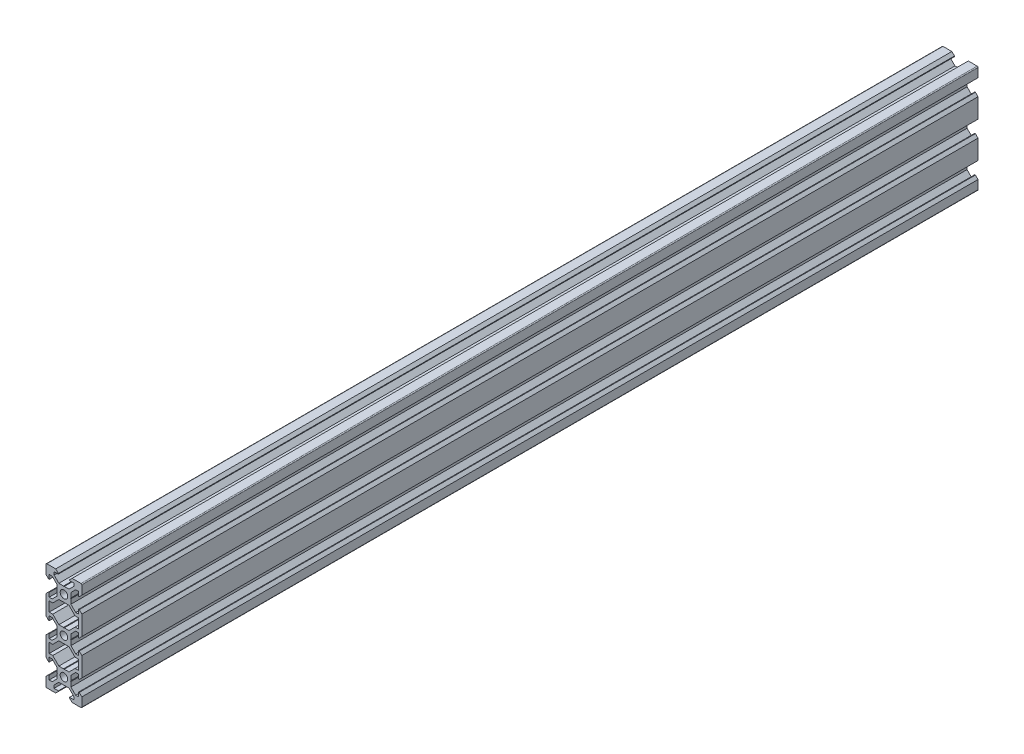
SolidWorks part; units mm, degrees
material "6063-T5"
ref_plane "Front Plane" through (0, 0, 0) normal (0, 0, 1) x (1, 0, 0)
ref_plane "Top Plane" through (0, 0, 0) normal (0, 1, 0) x (1, 0, 0)
ref_plane "Right Plane" through (0, 0, 0) normal (1, 0, 0) x (0, 0, -1)
sketch "Sketch2" plane through (0, 0, 0) normal (0, 0, 1) x (1, 0, 0)
  line L0 (-9.5, 10) -> (-4.58, 10)
  line L1 (-10, 10) -> (10, 10) construction
  line L2 (-10, 10) -> (-10, -10) construction
  line L3 (-10, -10) -> (10, -10) construction
  line L4 (10, 10) -> (10, -10) construction
  line L5 (-10, 10) -> (10, -10) construction
  line L6 (-10, -10) -> (10, 10) construction
  line L7 (-2.84, 3.9) -> (-0.21, 3.9)
  line L8 (-3.9, 2.84) -> (-3.9, 0.21)
  line L11 (-3.9, 3.9) -> (3.9, -3.9) construction
  line L12 (-3.9, -3.9) -> (3.9, 3.9) construction
  line L15 (-3.13, 8.2) -> (-5.5, 8.2)
  line L16 (-5.5, 8.2) -> (-5.5, 6.56)
  line L17 (0, 10) -> (0, -10) construction
  line L18 (-10, 0) -> (10, 0) construction
  line L20 (-10, 9.5) -> (-10, 4.58)
  line L21 (-10, 4.58) -> (-8.55, 3.13)
  line L22 (-8.55, 3.13) -> (-8.2, 3.13)
  line L27 (6.56, 5.5) -> (3.9, 2.84)
  line L30 (4.58, 10) -> (3.13, 8.55)
  line L35 (10, 4.58) -> (8.55, 3.13)
  line L36 (10, 9.5) -> (10, 4.58)
  line L37 (8.55, 3.13) -> (8.2, 3.13)
  line L40 (8.2, -5.5) -> (6.56, -5.5)
  line L41 (8.2, -3.13) -> (8.2, -5.5)
  line L42 (10, -4.58) -> (8.55, -3.13)
  line L43 (8.55, -3.13) -> (8.2, -3.13)
  line L44 (10, -10) -> (10, -4.58)
  line L57 (-8.2, -5.5) -> (-6.56, -5.5)
  line L58 (-8.2, -3.13) -> (-8.2, -5.5)
  line L59 (-10, -4.58) -> (-8.55, -3.13)
  line L60 (-10, -10) -> (-10, -4.58)
  line L61 (-8.55, -3.13) -> (-8.2, -3.13)
  line L62 (-0.21, 3.9) -> (0, 3.69)
  line L63 (0, 3.69) -> (0.21, 3.9)
  line L64 (0.21, 3.9) -> (2.84, 3.9)
  line L65 (3.69, 0) -> (3.9, -0.21)
  line L66 (3.9, 0.21) -> (3.69, 0)
  line L68 (0.21, -3.9) -> (0, -3.69)
  line L71 (3.9, -0.21) -> (3.9, -2.84)
  line L72 (-3.9, -0.21) -> (-3.9, -2.84)
  line L74 (-8.2, -7.3) -> (-8.2, -12.7)
  line L75 (-3.9, -39.79) -> (-3.69, -40)
  line L76 (-3.69, -40) -> (-3.9, -40.21)
  line L77 (-4.58, -10) -> (-3.13, -8.55) [skipped]
  line L78 (-0.21, -36.1) -> (0, -36.31)
  line L79 (-10, -10) -> (-4.58, -10) [skipped]
  line L80 (-2.84, -3.9) -> (-6.24, -7.3)
  line L82 (-8.2, -7.3) -> (-6.24, -7.3)
  line L84 (0, -36.31) -> (0.21, -36.1)
  line L85 (3.9, -39.79) -> (3.69, -40)
  line L86 (3.69, -40) -> (3.9, -40.21)
  line L87 (-0.21, -43.9) -> (0, -43.69)
  line L88 (0, -43.69) -> (0.21, -43.9)
  line L89 (-3.9, -39.79) -> (-3.9, -37.16)
  line L90 (2.84, -3.9) -> (6.24, -7.3)
  line L91 (8.2, -7.3) -> (8.2, -10)
  line L92 (6.24, -7.3) -> (8.2, -7.3)
  line L94 (-2.84, -16.1) -> (-0.21, -16.1)
  line L95 (-3.9, -17.16) -> (-3.9, -19.79)
  line L96 (-2.84, -23.9) -> (-0.21, -23.9)
  line L97 (3.9, -17.16) -> (3.9, -19.79)
  line L98 (2.84, -16.1) -> (6.24, -12.7)
  line L99 (-2.84, -16.1) -> (-6.24, -12.7)
  line L100 (0.21, -36.1) -> (2.84, -36.1)
  line L101 (8.2, -10) -> (8.2, -12.7)
  line L102 (6.24, -12.7) -> (8.2, -12.7)
  line L103 (-10, -10) -> (-10, -15.42)
  line L104 (-10, -15.42) -> (-8.55, -16.87)
  line L105 (-8.55, -16.87) -> (-8.2, -16.87)
  line L106 (-8.2, -16.87) -> (-8.2, -14.5)
  line L107 (-8.2, -14.5) -> (-6.56, -14.5)
  line L108 (-6.56, -14.5) -> (-3.9, -17.16)
  line L109 (-8.2, -12.7) -> (-6.24, -12.7)
  line L110 (6.56, -14.5) -> (3.9, -17.16)
  line L111 (4.58, -50) -> (3.13, -48.55)
  line L113 (-10, -30) -> (-10, -50) construction
  line L114 (-10, -50) -> (10, -50) construction
  line L115 (10, -30) -> (10, -50) construction
  line L116 (8.2, -14.5) -> (6.56, -14.5)
  line L117 (8.2, -16.87) -> (8.2, -14.5)
  line L118 (10, -15.42) -> (8.55, -16.87)
  line L119 (10, -10) -> (10, -15.42)
  line L120 (8.55, -16.87) -> (8.2, -16.87)
  line L121 (6.56, -25.5) -> (3.9, -22.84)
  line L122 (8.2, -25.5) -> (6.56, -25.5)
  line L123 (8.2, -23.13) -> (8.2, -25.5)
  line L124 (10, -24.58) -> (8.55, -23.13)
  line L125 (8.55, -23.13) -> (8.2, -23.13)
  line L126 (10, -30) -> (10, -24.58)
  line L127 (-6.56, -25.5) -> (-3.9, -22.84)
  line L128 (-8.2, -25.5) -> (-6.56, -25.5)
  line L129 (-8.2, -23.13) -> (-8.2, -25.5)
  line L130 (-10, -24.58) -> (-8.55, -23.13)
  line L131 (-10, -30) -> (-10, -24.58)
  line L132 (-8.55, -23.13) -> (-8.2, -23.13)
  line L133 (-0.21, -16.1) -> (0, -16.31)
  line L134 (0, -16.31) -> (0.21, -16.1)
  line L135 (0.21, -16.1) -> (2.84, -16.1)
  line L136 (3.69, -20) -> (3.9, -20.21)
  line L137 (3.9, -19.79) -> (3.69, -20)
  line L138 (0, -23.69) -> (-0.21, -23.9)
  line L139 (0.21, -23.9) -> (0, -23.69)
  line L140 (-3.69, -20) -> (-3.9, -19.79)
  line L141 (-3.9, -20.21) -> (-3.69, -20)
  line L142 (3.9, -20.21) -> (3.9, -22.84)
  line L143 (-3.9, -20.21) -> (-3.9, -22.84)
  line L144 (0.21, -23.9) -> (2.84, -23.9)
  line L145 (-2.84, -23.9) -> (-6.24, -27.3)
  line L146 (-8.2, -27.3) -> (-8.2, -32.7)
  line L147 (-8.2, -27.3) -> (-6.24, -27.3)
  line L148 (2.84, -23.9) -> (6.24, -27.3)
  line L149 (8.2, -27.3) -> (8.2, -30)
  line L150 (6.24, -27.3) -> (8.2, -27.3)
  line L151 (-10, -10) -> (10, -10) construction
  line L152 (-10, -10) -> (-10, -30) construction
  line L153 (-10, -30) -> (10, -30) construction
  line L154 (10, -10) -> (10, -30) construction
  line L155 (-10, -10) -> (10, -30) construction
  line L156 (-10, -30) -> (10, -10) construction
  line L157 (-3.9, -16.1) -> (3.9, -23.9) construction
  line L158 (-3.9, -23.9) -> (3.9, -16.1) construction
  line L159 (0, -10) -> (0, -30) construction
  line L160 (-10, -20) -> (10, -20) construction
  line L161 (3.9, -39.79) -> (3.9, -37.16)
  line L162 (0.21, -43.9) -> (2.84, -43.9)
  line L163 (-2.84, -3.9) -> (-0.21, -3.9)
  line L164 (3.9, 2.84) -> (3.9, 0.21)
  line L165 (-4.58, 10) -> (-3.13, 8.55)
  line L166 (-3.13, 8.55) -> (-3.13, 8.2)
  line L169 (-5.5, 6.56) -> (-2.84, 3.9)
  line L173 (-8.2, 3.13) -> (-8.2, 5.5)
  line L174 (-8.2, 5.5) -> (-6.56, 5.5)
  line L175 (-6.56, 5.5) -> (-3.9, 2.84)
  line L176 (5.5, 6.56) -> (2.84, 3.9)
  line L178 (5.5, 8.2) -> (5.5, 6.56)
  line L179 (3.13, 8.2) -> (5.5, 8.2)
  line L181 (3.13, 8.55) -> (3.13, 8.2)
  line L182 (8.2, 5.5) -> (6.56, 5.5)
  line L183 (8.2, 3.13) -> (8.2, 5.5)
  line L187 (6.56, -5.5) -> (3.9, -2.84)
  line L193 (-6.56, -5.5) -> (-3.9, -2.84)
  line L204 (0, -3.69) -> (-0.21, -3.9)
  line L206 (-3.69, 0) -> (-3.9, 0.21)
  line L207 (-3.9, -0.21) -> (-3.69, 0)
  line L210 (0.21, -3.9) -> (2.84, -3.9)
  line L213 (-10, 10) -> (-10, -10) construction
  line L214 (10, 10) -> (10, -10) construction
  line L215 (-10, 10) -> (10, -10) construction
  line L216 (-10, -10) -> (10, 10) construction
  line L217 (-3.9, 3.9) -> (3.9, -3.9) construction
  line L218 (-3.9, -3.9) -> (3.9, 3.9) construction
  line L219 (0, 10) -> (0, -10) construction
  line L220 (-10, 0) -> (10, 0) construction
  line L222 (9.5, 10) -> (4.58, 10)
  line L227 (3.13, -48.55) -> (3.13, -48.2)
  line L228 (3.13, -48.2) -> (5.5, -48.2)
  line L229 (5.5, -48.2) -> (5.5, -46.56)
  line L230 (-10, -50) -> (10, -30) construction
  line L231 (-10, -30) -> (10, -50) construction
  line L232 (0, -30) -> (0, -50) construction
  line L233 (-10, -40) -> (10, -40) construction
  line L234 (5.5, -46.56) -> (2.84, -43.9)
  line L235 (-2.84, -43.9) -> (-0.21, -43.9)
  line L236 (-3.9, -42.84) -> (-3.9, -40.21)
  line L237 (-2.84, -36.1) -> (-0.21, -36.1)
  line L238 (3.9, -42.84) -> (3.9, -40.21)
  line L239 (-3.9, -43.9) -> (3.9, -36.1) construction
  line L240 (-3.9, -36.1) -> (3.9, -43.9) construction
  line L241 (4.58, -50) -> (9.5, -50)
  line L242 (6.56, -45.5) -> (3.9, -42.84)
  line L243 (8.2, -45.5) -> (6.56, -45.5)
  line L244 (8.2, -43.13) -> (8.2, -45.5)
  line L245 (8.55, -43.13) -> (8.2, -43.13)
  line L246 (10, -44.58) -> (8.55, -43.13)
  line L247 (10, -44.58) -> (10, -49.5)
  line L248 (-4.58, -50) -> (-3.13, -48.55)
  line L249 (-3.13, -48.55) -> (-3.13, -48.2)
  line L250 (-3.13, -48.2) -> (-5.5, -48.2)
  line L251 (-5.5, -48.2) -> (-5.5, -46.56)
  line L252 (-5.5, -46.56) -> (-2.84, -43.9)
  line L253 (-4.58, -50) -> (-9.5, -50)
  line L254 (-8.55, -43.13) -> (-8.2, -43.13)
  line L255 (-6.56, -45.5) -> (-3.9, -42.84)
  line L256 (-8.2, -45.5) -> (-6.56, -45.5)
  line L257 (-8.2, -43.13) -> (-8.2, -45.5)
  line L258 (-10, -44.58) -> (-10, -49.5)
  line L259 (-10, -44.58) -> (-8.55, -43.13)
  line L260 (-8.2, -32.7) -> (-6.24, -32.7)
  line L261 (-2.84, -36.1) -> (-6.24, -32.7)
  line L262 (2.84, -36.1) -> (6.24, -32.7)
  line L263 (6.24, -32.7) -> (8.2, -32.7)
  line L264 (8.2, -32.7) -> (8.2, -30)
  line L265 (8.55, -36.87) -> (8.2, -36.87)
  line L266 (-8.55, -36.87) -> (-8.2, -36.87)
  line L267 (8.2, -36.87) -> (8.2, -34.5)
  line L268 (-8.2, -36.87) -> (-8.2, -34.5)
  line L269 (-8.2, -34.5) -> (-6.56, -34.5)
  line L270 (8.2, -34.5) -> (6.56, -34.5)
  line L271 (-6.56, -34.5) -> (-3.9, -37.16)
  line L272 (6.56, -34.5) -> (3.9, -37.16)
  line L273 (10, -35.42) -> (8.55, -36.87)
  line L274 (-10, -35.42) -> (-8.55, -36.87)
  line L275 (-10, -30) -> (-10, -35.42)
  line L276 (10, -30) -> (10, -35.42)
  line L307 (10, 10) -> (4.58, 10) [skipped]
  line L308 (-2.84, 3.9) -> (-0.21, 3.9) [skipped]
  line L309 (0.21, 3.9) -> (2.84, 3.9) [skipped]
  line L310 (-3.9, 2.84) -> (-3.9, 0.21) [skipped]
  line L311 (-3.9, -0.21) -> (-3.9, -2.84) [skipped]
  line L312 (3.9, -0.21) -> (3.9, -2.84) [skipped]
  line L313 (10, -4.58) -> (8.55, -3.13) [skipped]
  line L316 (-10, 10) -> (-10, 4.58) [skipped]
  line L317 (-10, -10) -> (-10, -4.58) [skipped]
  line L318 (-10, 4.58) -> (-8.55, 3.13) [skipped]
  line L319 (-8.55, 3.13) -> (-8.2, 3.13) [skipped]
  line L320 (8.55, 3.13) -> (8.2, 3.13) [skipped]
  line L321 (-8.2, -3.13) -> (-8.2, -5.5) [skipped]
  line L323 (2.84, -3.9) -> (6.24, -7.3) [skipped]
  line L324 (6.56, 5.5) -> (3.9, 2.84) [skipped]
  line L325 (-2.84, -3.9) -> (-6.24, -7.3) [skipped]
  line L326 (-10, -4.58) -> (-8.55, -3.13) [skipped]
  line L328 (8.2, -7.3) -> (8.2, -10) [skipped]
  line L329 (8.2, -3.13) -> (8.2, -5.5) [skipped]
  line L331 (10, 4.58) -> (8.55, 3.13) [skipped]
  line L332 (10, 10) -> (10, 4.58) [skipped]
  line L333 (10, -10) -> (10, -4.58) [skipped]
  line L334 (8.2, -5.5) -> (6.56, -5.5) [skipped]
  line L335 (-8.2, -5.5) -> (-6.56, -5.5) [skipped]
  line L336 (8.55, -3.13) -> (8.2, -3.13) [skipped]
  line L337 (-8.55, -3.13) -> (-8.2, -3.13) [skipped]
  line L338 (-0.21, 3.9) -> (0, 3.69) [skipped]
  line L339 (3.69, 0) -> (3.9, -0.21) [skipped]
  line L340 (-3.9, -0.21) -> (-3.69, 0) [skipped]
  line L341 (0, 3.69) -> (0.21, 3.9) [skipped]
  line L342 (3.9, 0.21) -> (3.69, 0) [skipped]
  line L343 (0, -3.69) -> (-0.21, -3.9) [skipped]
  line L344 (0.21, -3.9) -> (0, -3.69) [skipped]
  line L345 (-3.69, 0) -> (-3.9, 0.21) [skipped]
  line L346 (-8.2, -7.3) -> (-6.24, -7.3) [skipped]
  line L347 (6.24, -7.3) -> (8.2, -7.3) [skipped]
  circle A1 centre (0, -20) radius 2.1
  circle A2 centre (0, 0) radius 2.1
  circle A3 centre (0, -40) radius 2.1
  arc A4 (9.5, -50) -> (10, -49.5) centre (9.5, -49.5) ccw
  arc A5 (-9.5, -50) -> (-10, -49.5) centre (-9.5, -49.5) cw
  arc A6 (10, 9.5) -> (9.5, 10) centre (9.5, 9.5) ccw
  arc A7 (-9.5, 10) -> (-10, 9.5) centre (-9.5, 9.5) ccw
  point P0 (0, 0)
  point P6 (0, 0)
  point P19 (0, 0)
  point P22 (0, 0)
  point P67 (0, -20)
  point P73 (0, 0)
  point P86 (0, 0)
  point P111 (0, -20)
  point P124 (0, -20)
  point P127 (0, -20)
  point P171 (0, -20)
  point P184 (0, -20)
  point P185 (0, 0)
  point P190 (0, 0)
  point P203 (0, 0)
  point P206 (0, 0)
  point P242 (0, -40)
  point P250 (0, 0)
  point P263 (0, 0)
  point P289 (-8.2, -30)
  point P365 (-8.2, -30)
  dimension "D8" = 0.5
  dimension "D3" = 0.21
  dimension "D4" = 45
  dimension "D5" = 0.21
  dimension "D6" = 0.21
  dimension "D7" = 0.21
  dimension "D13" = 0.21
  dimension "D22" = 3.13
  dimension "D23" = 0.35
  dimension "D24" = 1.64
  dimension "D18" = 2
  dimension "D19" = 2
  dimension "D11" = 4
  dimension "D15" = 4
extrude "Boss-Extrude2" add sketch "Sketch2" against normal blind 500
